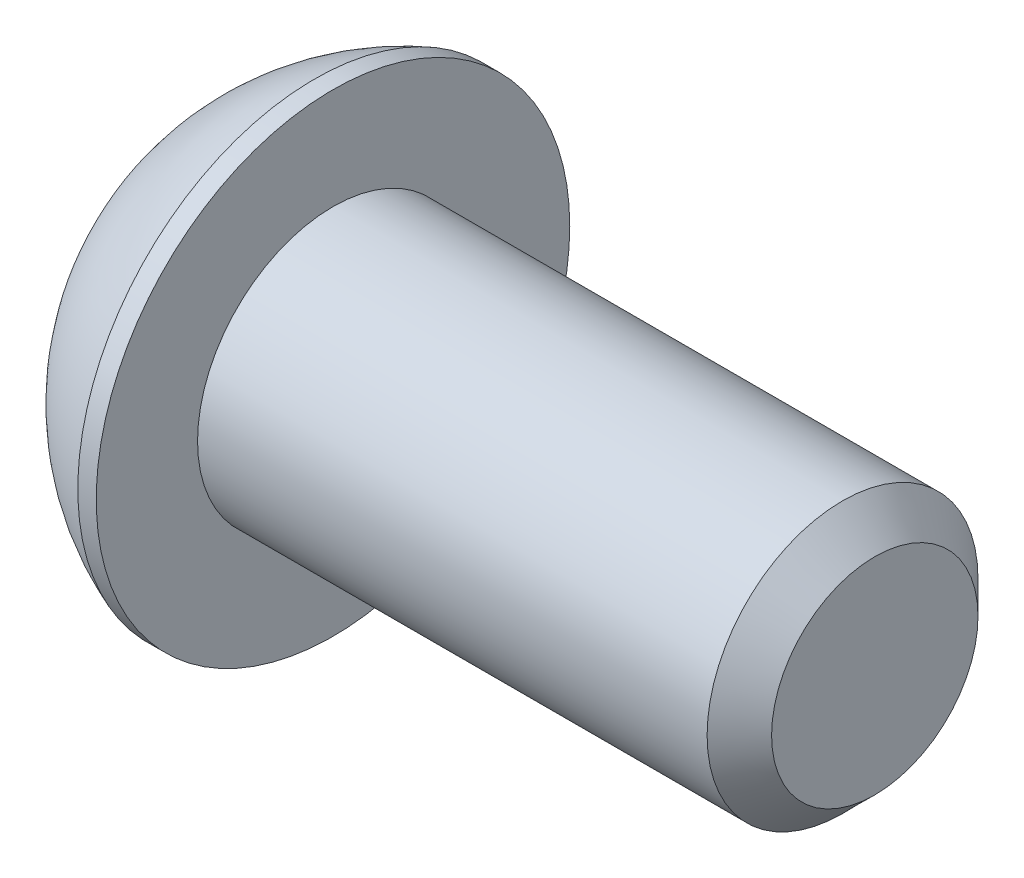
SolidWorks part; units mm, degrees
ref_plane "Front Plane" through (0, 0, 0) normal (0, 0, 1) x (1, 0, 0)
ref_plane "Top Plane" through (0, 0, 0) normal (0, 1, 0) x (1, 0, 0)
ref_plane "Right Plane" through (0, 0, 0) normal (1, 0, 0) x (0, 0, -1)
sketch "Sketch1" plane through (0, 0, 0) normal (0, 0, 1) x (1, 0, 0)
  line L0 (-3.3528, 3.175) -> (-3.3528, 0)
  line L1 (-3.3528, 0) -> (0, 0)
  line L2 (0, 0) -> (0, 5.5499)
  line L3 (0, 5.5499) -> (-0.4318, 5.5499)
  line L4 (-3.3528, 0) -> (0, 0) construction
  arc A0 (-0.4318, 5.5499) -> (-3.3528, 3.175) centre (1.6473, 0.0089) ccw
revolve "Revolve1" add sketch "Sketch1" angle 360 about L4
sketch "Sketch2" plane through (0, 0, 0) normal (1, 0, 0) x (0, 0, -1)
  circle A0 centre (0, 0) radius 3.175
extrude "Boss-Extrude1" add sketch "Sketch2" along normal blind 12.7
sketch "Sketch3" plane through (-3.3528, 0, 0) normal (-1, 0, 0) x (0, 0, 1)
  line L0 (2.2914, 0) -> (1.1457, 1.9844)
  line L1 (1.1457, 1.9844) -> (-1.1457, 1.9844)
  line L2 (-1.1457, 1.9844) -> (-2.2914, 0)
  line L3 (-2.2914, 0) -> (-1.1457, -1.9844)
  line L4 (-1.1457, -1.9844) -> (1.1457, -1.9844)
  line L5 (1.1457, -1.9844) -> (2.2914, 0)
extrude "Cut-Extrude1" cut sketch "Sketch3" against normal blind 2.2225
chamfer "Chamfer1" distance 0.7557 angle 45 1 edges at (12.7, 0, -3.175)
